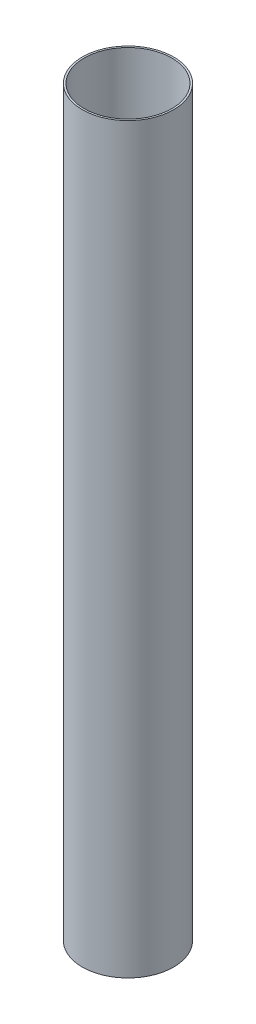
SolidWorks part; units mm, degrees
ref_plane "Front Plane" through (0, 0, 0) normal (0, 0, 1) x (1, 0, 0)
ref_plane "Top Plane" through (0, 0, 0) normal (0, 1, 0) x (1, 0, 0)
ref_plane "Right Plane" through (0, 0, 0) normal (1, 0, 0) x (0, 0, -1)
sketch "Sketch1" plane through (0, 0, 0) normal (0, 0, 1) x (1, 0, 0)
  line L0 (49.53, 0) -> (51.5874, 0)
  line L1 (51.5874, 0) -> (51.5874, 838.2)
  line L2 (51.5874, 838.2) -> (49.53, 838.2)
  line L7 (49.53, 0) -> (49.53, 838.2)
  point P0 (49.53, 9.8309)
  dimension "D1" = 49.53
  dimension "D2" = 2.0574
  dimension "D3" = 838.2
  dimension "D4" = 0
ref_axis "Central Axis" through (0, 123.6201, 0) along (0, -1, 0)
revolve "Revolve1" add sketch "Sketch1" angle 360 about axis through (0, 123.6201, 0) along (0, -1, 0)
